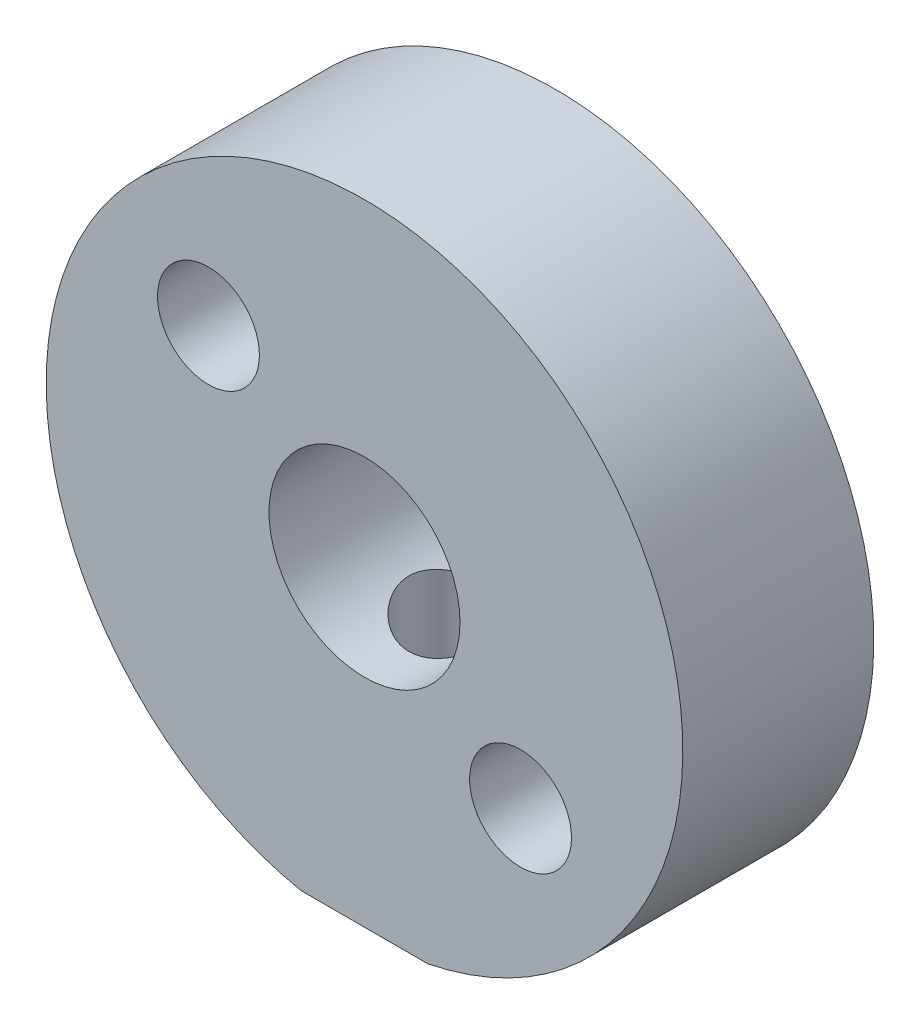
SolidWorks part; units mm, degrees
ref_plane "Front Plane" through (0, 0, 0) normal (0, 0, 1) x (1, 0, 0)
ref_plane "Top Plane" through (0, 0, 0) normal (0, 1, 0) x (1, 0, 0)
ref_plane "Right Plane" through (0, 0, 0) normal (1, 0, 0) x (0, 0, -1)
sketch "Sketch1" plane through (0, 0, 0) normal (0, 0, 1) x (1, 0, 0)
  circle A0 centre (0, 0) radius 5
  circle A1 centre (0, 0) radius 1.5
extrude "Extrude1" add sketch "Sketch1" along normal mid plane 3
sketch "Sketch2" plane through (0, 0, 0) normal (0, 0, 1) x (1, 0, 0)
  line L0 (-2.4513, 2.0569) -> (0, 0)
  circle A0 centre (0, 0) radius 3.2 construction
  circle A1 centre (-2.4513, 2.0569) radius 0.8
  circle A4 centre (2.4513, -2.0569) radius 0.8
  circle A6 centre (-2.0569, -2.4513) radius 0.8 [skipped]
  circle A7 centre (2.0569, 2.4513) radius 0.8 [skipped]
  dimension "D1" = 4
  dimension "D2" = 6.4
extrude "Extrude2" cut sketch "Sketch2" against normal through all both and the other way through all
sketch "Sketch3" plane through (0, 0, 0) normal (0, 1, 0) x (1, 0, 0)
  circle A0 centre (0, 0) radius 0.8
extrude "Extrude3" cut sketch "Sketch3" against normal through all
sketch "Sketch4" plane through (0, 0, 0) normal (0, 0, 1) x (1, 0, 0)
  line L0 (0, 0) -> (0, -4.9)
  line L2 (0, -4.9) -> (-4.2055, -4.9)
  line L3 (0, -4.9) -> (0, -5.4728)
  line L4 (0, -5.4728) -> (-4.2055, -5.4728)
  line L5 (-4.2055, -4.9) -> (-4.2055, -5.4728)
  line L6 (0, -4.9) -> (4.0922, -4.9)
  line L7 (0, -4.9) -> (0, -5.4728)
  line L8 (0, -5.4728) -> (4.0922, -5.4728)
  line L9 (4.0922, -4.9) -> (4.0922, -5.4728)
extrude "Extrude4" cut sketch "Sketch4" against normal through all both and the other way through all contours L2 L5 L4 L3 | L9 L6 L3 L8
